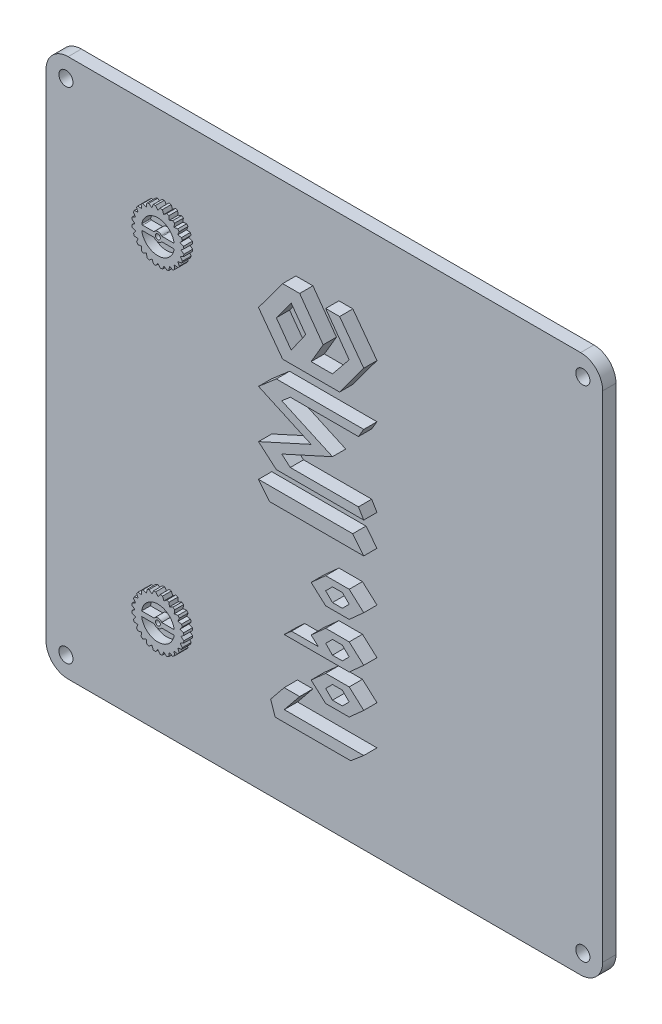
SolidWorks part; units mm, degrees
ref_plane "Front Plane" through (0, 0, 0) normal (0, 0, 1) x (1, 0, 0)
ref_plane "Top Plane" through (0, 0, 0) normal (0, 1, 0) x (1, 0, 0)
ref_plane "Right Plane" through (0, 0, 0) normal (1, 0, 0) x (0, 0, -1)
other "Centro da massa"
sketch "Sketch1" plane through (0, 0, 0) normal (0, 0, 1) x (1, 0, 0)
  line L1 (63, 61) -> (-63, 61)
  line L2 (63, 61) -> (63, -61)
  line L3 (63, -61) -> (-63, -61)
  line L4 (-63, 61) -> (-63, -61)
  line L5 (63, 61) -> (-63, -61) construction
  line L6 (63, -61) -> (-63, 61) construction
  point P0 (0, 0)
  dimension "D1" = 126
  dimension "D2" = 122
extrude "Boss-Extrude1" add sketch "Sketch1" along normal blind 3
sketch "Esboço8" plane through (0, 0, 3) normal (0, 0, 1) x (1, 0, 0)
  line L9 (-8.1446, -42.0239) -> (8.9552, -42.0239)
  line L15 (-6.0773, -39.5239) -> (-2.5948, -35.2227)
  line L36 (3.2914, 43.791) -> (6.4479, 43.791)
  line L47 (11.9079, -39.5239) -> (-6.0773, -39.5239)
  line L51 (11.9079, -30.6806) -> (8.6165, -27.7268)
  line L52 (3.2914, -27.7268) -> (0, -30.6806)
  line L53 (0, -30.6806) -> (3.2914, -33.6344)
  line L54 (8.6165, -33.6344) -> (11.9079, -30.6806)
  line L55 (0, -30.6806) -> (11.9079, -30.6806) construction
  line L56 (4.8336, -32.2228) -> (3.2914, -30.6806)
  line L57 (3.2914, -30.6806) -> (4.8336, -29.1384)
  line L58 (7.0744, -29.1384) -> (8.6165, -30.6806)
  line L59 (8.6165, -30.6806) -> (7.0744, -32.2228)
  line L68 (3.2914, -27.7268) -> (8.6165, -27.7268)
  line L69 (3.2914, -33.6344) -> (8.6165, -33.6344)
  line L70 (4.8336, -29.1384) -> (7.0744, -29.1384)
  line L71 (4.8336, -32.2228) -> (7.0744, -32.2228)
  line L72 (3.2914, -24.8048) -> (8.6165, -24.8048)
  line L73 (11.9079, -21.851) -> (8.6165, -24.8048)
  line L74 (8.6165, -18.8972) -> (11.9079, -21.851)
  line L75 (3.2914, -18.8972) -> (8.6165, -18.8972)
  line L76 (0, -21.851) -> (3.2914, -18.8972)
  line L77 (1.6457, -23.3279) -> (0, -21.851)
  line L78 (4.8336, -23.3932) -> (7.0744, -23.3932)
  line L79 (7.0744, -23.3932) -> (8.6165, -21.851)
  line L80 (8.6165, -21.851) -> (7.0744, -20.3088)
  line L81 (4.8336, -20.3088) -> (7.0744, -20.3088)
  line L82 (4.8336, -20.3088) -> (3.2914, -21.851)
  line L83 (3.2914, -21.851) -> (4.8336, -23.3932)
  line L84 (3.2914, -24.8048) -> (-6.0773, -24.8048)
  line L85 (-6.0773, -24.8048) -> (-4.4316, -23.3279)
  line L86 (-4.4316, -23.3279) -> (1.6457, -23.3279)
  line L87 (-2.5948, -35.2227) -> (-6.0948, -35.2227)
  line L94 (3.2914, -14.4937) -> (8.6165, -14.4937)
  line L95 (8.6165, -14.4937) -> (11.9079, -11.5399)
  line L96 (11.9079, -11.5399) -> (8.6165, -8.5862)
  line L97 (3.2914, -8.5862) -> (8.6165, -8.5862)
  line L98 (3.2914, -8.5862) -> (0, -11.5399)
  line L99 (0, -11.5399) -> (3.2914, -14.4937)
  line L100 (8.6165, -11.5399) -> (7.0744, -13.0821)
  line L101 (7.0744, -9.9978) -> (8.6165, -11.5399)
  line L102 (4.8336, -9.9978) -> (7.0744, -9.9978)
  line L103 (3.2914, -11.5399) -> (4.8336, -9.9978)
  line L104 (4.8336, -13.0821) -> (3.2914, -11.5399)
  line L105 (4.8336, -13.0821) -> (7.0744, -13.0821)
  line L106 (-6.0948, -35.2227) -> (-9.1643, -39.0137)
  line L107 (-9.1643, -39.0137) -> (-8.1446, -42.0239)
  line L108 (11.9079, 6.6223) -> (-7.8765, 6.6223)
  line L109 (9.4156, 2.7015) -> (11.9079, -0.4117)
  line L110 (11.9079, -0.4117) -> (-9.4091, -0.4117)
  line L111 (-9.4091, -0.4117) -> (-11.9079, 2.7015)
  line L112 (-11.9079, 2.7015) -> (9.4156, 2.7015)
  line L113 (-7.8765, 6.6223) -> (-11.9079, 10.097)
  line L114 (-11.9079, 10.097) -> (0, 15.5092)
  line L116 (4.8336, 15.5092) -> (-6.6491, 10.2903)
  line L117 (-6.6491, 10.2903) -> (-4.7138, 8.6223)
  line L118 (-4.7138, 8.6223) -> (10.7124, 8.6223)
  line L119 (10.7124, 8.6223) -> (11.9079, 6.6223)
  line L120 (-11.9079, 36.3884) -> (-6.4479, 28.9858)
  line L121 (10.7124, 22.3961) -> (11.9079, 24.3961)
  line L122 (-4.7138, 22.3961) -> (10.7124, 22.3961)
  line L123 (11.9079, 24.3961) -> (-7.8765, 24.3961)
  line L124 (-6.6491, 20.7281) -> (-4.7138, 22.3961)
  line L125 (-7.8765, 24.3961) -> (-11.9079, 20.9215)
  line L126 (4.8336, 15.5092) -> (-6.6491, 20.7281)
  line L127 (-11.9079, 20.9215) -> (0, 15.5092)
  line L128 (-6.4479, 28.9858) -> (6.4479, 28.9858)
  line L129 (6.4479, 28.9858) -> (11.9079, 36.3884)
  line L130 (6.4479, 43.791) -> (11.9079, 36.3884)
  line L131 (-6.4479, 43.791) -> (-2.5948, 43.791)
  line L132 (-11.9079, 36.3884) -> (-6.4479, 43.791)
  line L133 (4.8215, 31.7256) -> (8.6165, 36.3884)
  line L134 (2.7303, 36.3884) -> (0, 31.7256)
  line L135 (0, 31.7256) -> (4.8215, 31.7256)
  line L136 (8.6165, 36.3884) -> (3.2914, 43.791)
  line L137 (3.2914, 43.791) -> (6.4479, 43.791)
  line L138 (2.7303, 36.3884) -> (-2.5948, 43.791)
  line L148 (11.9079, -39.5239) -> (8.9552, -42.0239)
  line L151 (-4.5103, 31.7256) -> (-1.2273, 36.3884)
  line L153 (-1.2273, 36.3884) -> (-4.5103, 40.9523)
  line L154 (-4.5103, 40.9523) -> (-7.8765, 36.3884)
  line L155 (-7.8765, 36.3884) -> (-4.5103, 31.7256)
  point P89 (10.2622, -13.0168)
  dimension "D3" = 3.5
  dimension "D5" = 2
  dimension "D6" = 2
extrude "Ressalto-extrusão3" add sketch "Esboço8" along normal blind 3 contours L148 L47 L15 L87 L106 L107 L9 | L52 L55 L57 L70 L58 L51 L68 | L55 L53 L69 L54 L59 L71 L56 | L86 L85 L84 L72 L73 L74 L75 L76 L77 L83 L82 L81 L80 L79 L78 | L98 L99 L94 L95 L96 L97 L105 L104 L103 L102 L101 L100 | L112 L111 L110 L109 | L125 L127 L114 L113 L108 L119 L118 L117 L116 L126 L124 L122 L121 L123 | L134 L138 L131 L132 L120 L128 L129 L130 L36 L136 L133 L135 L155 L154 L153 L151
sketch "Esboço10" plane through (0, 0, 3) normal (0, 0, 1) x (1, 0, 0)
  line L2 (-30.6628, 39.2244) -> (-29.8737, 38.9014)
  line L3 (-29.8737, 38.9014) -> (-29.8057, 38.4014)
  line L4 (-29.8057, 38.4014) -> (-30.4799, 37.8795)
  line L5 (-30.4799, 37.8795) -> (-29.8057, 37.9207) construction
  line L6 (-30.1466, 39.903) -> (-30.6628, 39.2244)
  line L7 (-31.1874, 40.4761) -> (-30.3417, 40.3684)
  line L8 (-30.3417, 40.3684) -> (-30.1466, 39.903)
  line L9 (-30.8645, 41.2652) -> (-31.1874, 40.4761)
  line L10 (-32.0182, 41.5494) -> (-31.1734, 41.6642)
  line L11 (-31.1734, 41.6642) -> (-30.8645, 41.2652)
  line L12 (-31.9105, 42.3951) -> (-32.0182, 41.5494)
  line L13 (-33.0984, 42.371) -> (-32.3121, 42.7006)
  line L14 (-32.3121, 42.7006) -> (-31.9105, 42.3951)
  line L15 (-33.2133, 43.2159) -> (-33.0984, 42.371)
  line L16 (-34.3545, 42.8851) -> (-33.6803, 43.407)
  line L17 (-33.6803, 43.407) -> (-33.2133, 43.2159)
  line L18 (-34.6841, 43.6714) -> (-34.3545, 42.8851)
  line L19 (-35.7009, 43.0566) -> (-35.1847, 43.7352)
  line L20 (-35.1847, 43.7352) -> (-34.6841, 43.6714)
  line L21 (-36.2228, 43.7308) -> (-35.7009, 43.0566)
  line L22 (-37.0457, 42.8737) -> (-36.7228, 43.6628)
  line L23 (-36.7228, 43.6628) -> (-36.2228, 43.7308)
  line L24 (-37.7243, 43.3899) -> (-37.0457, 42.8737)
  line L25 (-38.2974, 42.3491) -> (-38.1897, 43.1948)
  line L26 (-38.1897, 43.1948) -> (-37.7243, 43.3899)
  line L27 (-39.0865, 42.672) -> (-38.2974, 42.3491)
  line L28 (-39.3707, 41.5183) -> (-39.4855, 42.3631)
  line L29 (-39.4855, 42.3631) -> (-39.0865, 42.672)
  line L30 (-40.2165, 41.626) -> (-39.3707, 41.5183)
  line L31 (-40.1924, 40.4381) -> (-40.522, 41.2244)
  line L32 (-40.522, 41.2244) -> (-40.2165, 41.626)
  line L33 (-41.0372, 40.3232) -> (-40.1924, 40.4381)
  line L34 (-40.7064, 39.182) -> (-41.2283, 39.8562)
  line L35 (-41.2283, 39.8562) -> (-41.0372, 40.3232)
  line L36 (-41.4928, 38.8524) -> (-40.7064, 39.182)
  line L37 (-40.8779, 37.8356) -> (-41.5565, 38.3518)
  line L38 (-41.5565, 38.3518) -> (-41.4928, 38.8524)
  line L39 (-41.5521, 37.3137) -> (-40.8779, 37.8356)
  line L40 (-40.6951, 36.4908) -> (-41.4842, 36.8137)
  line L41 (-41.4842, 36.8137) -> (-41.5521, 37.3137)
  line L42 (-41.2112, 35.8122) -> (-40.6951, 36.4908)
  line L43 (-40.1704, 35.2391) -> (-41.0162, 35.3468)
  line L44 (-41.0162, 35.3468) -> (-41.2112, 35.8122)
  line L45 (-40.4933, 34.45) -> (-40.1704, 35.2391)
  line L46 (-39.3396, 34.1658) -> (-40.1845, 34.051)
  line L47 (-40.1845, 34.051) -> (-40.4933, 34.45)
  line L48 (-39.4473, 33.32) -> (-39.3396, 34.1658)
  line L49 (-38.2594, 33.3442) -> (-39.0457, 33.0145)
  line L50 (-39.0457, 33.0145) -> (-39.4473, 33.32)
  line L51 (-38.1445, 32.4993) -> (-38.2594, 33.3442)
  line L52 (-37.0033, 32.8301) -> (-37.6775, 32.3082)
  line L53 (-37.6775, 32.3082) -> (-38.1445, 32.4993)
  line L54 (-36.6737, 32.0437) -> (-37.0033, 32.8301)
  line L55 (-35.657, 32.6586) -> (-36.1731, 31.98)
  line L56 (-36.1731, 31.98) -> (-36.6737, 32.0437)
  line L57 (-35.1351, 31.9844) -> (-35.657, 32.6586)
  line L58 (-34.3121, 32.8414) -> (-34.6351, 32.0523)
  line L59 (-34.6351, 32.0523) -> (-35.1351, 31.9844)
  line L60 (-33.6335, 32.3253) -> (-34.3121, 32.8414)
  line L61 (-33.0604, 33.3661) -> (-33.1681, 32.5203)
  line L62 (-33.1681, 32.5203) -> (-33.6335, 32.3253)
  line L63 (-32.2713, 33.0432) -> (-33.0604, 33.3661)
  line L64 (-31.9872, 34.1969) -> (-31.8723, 33.352)
  line L65 (-31.8723, 33.352) -> (-32.2713, 33.0432)
  line L66 (-31.1414, 34.0892) -> (-31.9872, 34.1969)
  line L67 (-31.1655, 35.2771) -> (-30.8359, 34.4908)
  line L68 (-30.8359, 34.4908) -> (-31.1414, 34.0892)
  line L69 (-30.3206, 35.392) -> (-31.1655, 35.2771)
  line L70 (-30.6514, 36.5332) -> (-30.1295, 35.859)
  line L71 (-30.1295, 35.859) -> (-30.3206, 35.392)
  line L72 (-29.8651, 36.8628) -> (-30.6514, 36.5332)
  line L73 (-30.4799, 37.8795) -> (-29.8013, 37.3634)
  line L74 (-29.8013, 37.3634) -> (-29.8651, 36.8628)
  line L77 (-34.8245, 38.4014) -> (-31.9963, 38.4014)
  line L78 (-31.9963, 38.4014) -> (-34.8245, 38.4014)
  line L79 (-36.5333, 38.4014) -> (-39.3615, 38.4014)
  line L80 (-36.5333, 37.3137) -> (-39.3615, 37.3137)
  line L81 (-34.8245, 37.3137) -> (-31.9963, 37.3137)
  circle A0 centre (-35.6789, 37.8576) radius 3.7225
  circle A2 centre (-35.6789, 37.8576) radius 1.0128
  circle A3 centre (-35.6789, 37.8576) radius 0.5545
  point P13 (-30.6628, 39.2244)
  point P14 (-30.4799, 37.8795)
  point P109 (-35.6789, 37.8576)
  dimension "D1" = 120
  dimension "D2" = 120
  dimension "D3" = 0.5
  dimension "D4" = 24
extrude "Ressalto-extrusão4" add sketch "Esboço10" along normal blind 2 contours L74 L73 L4 L3 L2 L6 L8 L7 L9 L11 L10 L12 L14 L13 L15 L17 L16 L18 L20 L19 L21 L23 L22 L24 L26 L25 L27 L29 L28 L30 L32 L31 L33 L35 L34 L36 L38 L37 L39 L41 L40 L42 L44 L43 L45 L47 L46 L48 L50 L49 L51 | A2 L81 A0 L77 | A2 L79 A0 L80 | A2 A3
fillet "Filete8" radius 0.2 4 edges at (-39.3615, 38.4014, 4) (-39.3615, 37.3137, 4) (-31.9963, 37.3137, 4) (-31.9963, 38.4014, 4)
fillet "Filete9" radius 0.2 4 edges at (-34.8245, 37.3137, 4) (-36.5333, 37.3137, 4) (-36.5333, 38.4014, 4) (-34.8245, 38.4014, 4)
sketch "Sketch2" plane through (0, 0, 3) normal (0, 0, 1) x (1, 0, 0)
  line L0 (-63, 61) -> (-63, -61) construction
  line L3 (-63, -61) -> (63, -61) construction
  circle A0 centre (-58.5, -56.5) radius 1.6
  dimension "D1" = 3.2
  dimension "D3" = 4.5
  dimension "D2" = 4.5
extrude "Cut-Extrude1" cut sketch "Sketch2" against normal up to surface (3 mm away) up to face at (0, 0, 0)
pattern_linear "LPattern1" count 2 spacing 113 along (0, 1, 0) count 2 spacing 117 along (1, 0, 0) of "Cut-Extrude1"
fillet "Fillet1" radius 5 4 edges at (-63, 61, 1.5) (63, 61, 1.5) (63, -61, 1.5) (-63, -61, 1.5)
mirror "Mirror1" about plane through (0, 0, 0) normal (0, 1, 0) of "Ressalto-extrusão4"
sketch "Sketch3" plane through (0, 0, 0) normal (0, 0, -1) x (-1, 0, 0)
  line L0 (-58.835, 51.3559) -> (-58.835, -7.5812) construction
  text T0 "Fran\r\n" font "Bauhaus 93" height 10
extrude "Cut-Extrude2" cut sketch "Sketch3" against normal offset from surface (2 mm away) 1 up to face at (60.1, 56.5, 3)
